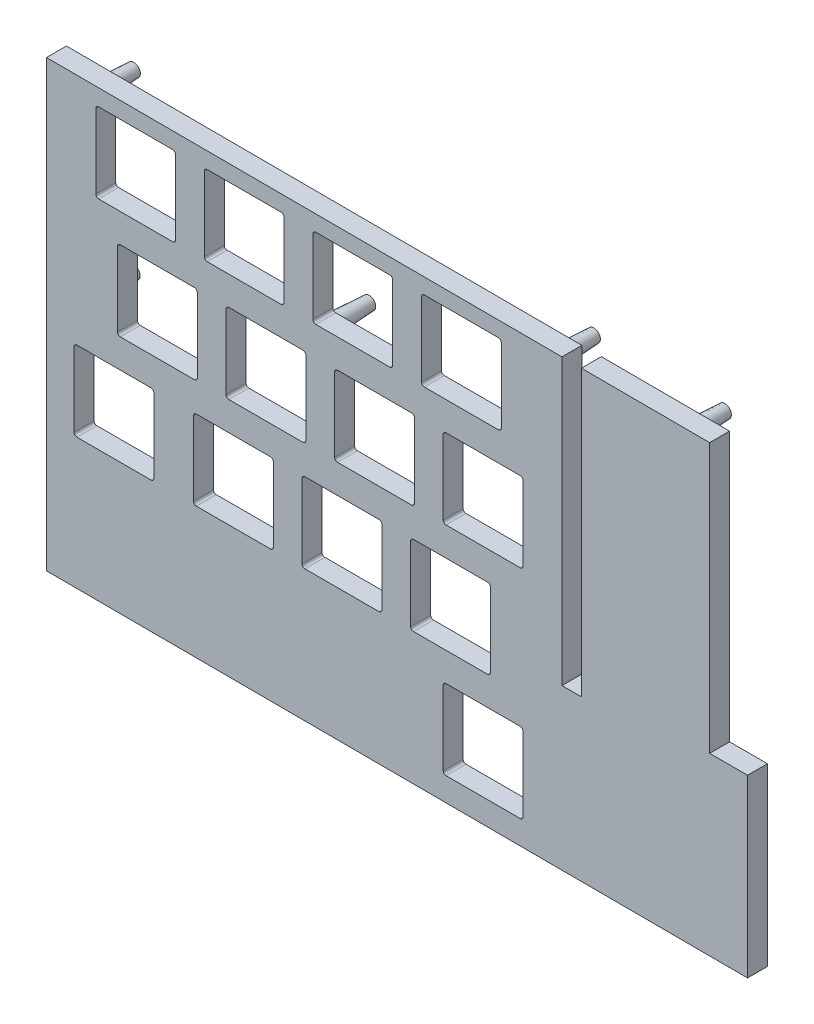
SolidWorks part; units mm, degrees
ref_plane "Front Plane" through (0, 0, 0) normal (0, 0, 1) x (1, 0, 0)
ref_plane "Top Plane" through (0, 0, 0) normal (0, 1, 0) x (1, 0, 0)
ref_plane "Right Plane" through (0, 0, 0) normal (1, 0, 0) x (0, 0, -1)
sketch "Model" plane through (0, 0, 0) normal (0, 0, 1) x (1, 0, 0)
  line L0 (9.145, -2.923) -> (22.145, -2.923)
  line L1 (9.145, -16.923) -> (22.145, -16.923)
  line L2 (8.645, -3.423) -> (8.645, -16.423)
  line L3 (22.645, -3.423) -> (22.645, -16.423)
  line L4 (28.195, -2.923) -> (41.195, -2.923)
  line L5 (28.195, -16.923) -> (41.195, -16.923)
  line L6 (27.695, -3.423) -> (27.695, -16.423)
  line L7 (41.695, -3.423) -> (41.695, -16.423)
  line L8 (47.245, -2.923) -> (60.245, -2.923)
  line L9 (47.245, -16.923) -> (60.245, -16.923)
  line L10 (46.745, -3.423) -> (46.745, -16.423)
  line L11 (60.745, -3.423) -> (60.745, -16.423)
  line L12 (66.295, -2.923) -> (79.295, -2.923)
  line L13 (66.295, -16.923) -> (79.295, -16.923)
  line L14 (65.795, -3.423) -> (65.795, -16.423)
  line L15 (79.795, -3.423) -> (79.795, -16.423)
  line L16 (12.955, -21.973) -> (25.955, -21.973)
  line L17 (12.955, -35.973) -> (25.955, -35.973)
  line L18 (12.455, -22.473) -> (12.455, -35.473)
  line L19 (26.455, -22.473) -> (26.455, -35.473)
  line L20 (32.005, -21.973) -> (45.005, -21.973)
  line L21 (32.005, -35.973) -> (45.005, -35.973)
  line L22 (31.505, -22.473) -> (31.505, -35.473)
  line L23 (45.505, -22.473) -> (45.505, -35.473)
  line L24 (51.055, -21.973) -> (64.055, -21.973)
  line L25 (51.055, -35.973) -> (64.055, -35.973)
  line L26 (50.555, -22.473) -> (50.555, -35.473)
  line L27 (64.555, -22.473) -> (64.555, -35.473)
  line L28 (70.105, -21.973) -> (83.105, -21.973)
  line L29 (70.105, -35.973) -> (83.105, -35.973)
  line L30 (69.605, -22.473) -> (69.605, -35.473)
  line L31 (83.605, -22.473) -> (83.605, -35.473)
  line L32 (5.335, -41.023) -> (18.335, -41.023)
  line L33 (5.335, -55.023) -> (18.335, -55.023)
  line L34 (4.835, -41.523) -> (4.835, -54.523)
  line L35 (18.835, -41.523) -> (18.835, -54.523)
  line L36 (26.29, -41.023) -> (39.29, -41.023)
  line L37 (26.29, -55.023) -> (39.29, -55.023)
  line L38 (25.79, -41.523) -> (25.79, -54.523)
  line L39 (39.79, -41.523) -> (39.79, -54.523)
  line L40 (45.34, -41.023) -> (58.34, -41.023)
  line L41 (45.34, -55.023) -> (58.34, -55.023)
  line L42 (44.84, -41.523) -> (44.84, -54.523)
  line L43 (58.84, -41.523) -> (58.84, -54.523)
  line L44 (64.39, -41.023) -> (77.39, -41.023)
  line L45 (64.39, -55.023) -> (77.39, -55.023)
  line L46 (63.89, -41.523) -> (63.89, -54.523)
  line L47 (77.89, -41.523) -> (77.89, -54.523)
  line L48 (70.105, -60.073) -> (83.105, -60.073)
  line L49 (70.105, -74.073) -> (83.105, -74.073)
  line L50 (69.605, -60.573) -> (69.605, -73.573)
  line L51 (83.605, -60.573) -> (83.605, -73.573)
  line L52 (61.667, -61.073) -> (67.667, -61.073)
  line L53 (61.667, -76.073) -> (67.667, -76.073)
  line L54 (61.167, -61.573) -> (61.167, -75.573)
  line L55 (68.167, -61.573) -> (68.167, -75.573)
  line L56 (85.543, -61.073) -> (91.543, -61.073)
  line L57 (85.543, -76.073) -> (91.543, -76.073)
  line L58 (85.043, -61.573) -> (85.043, -75.573)
  line L59 (92.043, -61.573) -> (92.043, -75.573)
  line L60 (0, -78) -> (123, -78.3615)
  line L61 (0, 0) -> (123, -0.3615)
  line L62 (0, -78) -> (0, 0)
  line L63 (123, -78.3615) -> (123, -0.3615)
  arc A0 (9.145, -2.923) -> (8.645, -3.423) centre (9.145, -3.423) ccw
  arc A1 (22.645, -3.423) -> (22.145, -2.923) centre (22.145, -3.423) ccw
  arc A2 (8.645, -16.423) -> (9.145, -16.923) centre (9.145, -16.423) ccw
  arc A3 (22.145, -16.923) -> (22.645, -16.423) centre (22.145, -16.423) ccw
  arc A4 (28.195, -2.923) -> (27.695, -3.423) centre (28.195, -3.423) ccw
  arc A5 (41.695, -3.423) -> (41.195, -2.923) centre (41.195, -3.423) ccw
  arc A6 (27.695, -16.423) -> (28.195, -16.923) centre (28.195, -16.423) ccw
  arc A7 (41.195, -16.923) -> (41.695, -16.423) centre (41.195, -16.423) ccw
  arc A8 (47.245, -2.923) -> (46.745, -3.423) centre (47.245, -3.423) ccw
  arc A9 (60.745, -3.423) -> (60.245, -2.923) centre (60.245, -3.423) ccw
  arc A10 (46.745, -16.423) -> (47.245, -16.923) centre (47.245, -16.423) ccw
  arc A11 (60.245, -16.923) -> (60.745, -16.423) centre (60.245, -16.423) ccw
  arc A12 (66.295, -2.923) -> (65.795, -3.423) centre (66.295, -3.423) ccw
  arc A13 (79.795, -3.423) -> (79.295, -2.923) centre (79.295, -3.423) ccw
  arc A14 (65.795, -16.423) -> (66.295, -16.923) centre (66.295, -16.423) ccw
  arc A15 (79.295, -16.923) -> (79.795, -16.423) centre (79.295, -16.423) ccw
  arc A16 (12.955, -21.973) -> (12.455, -22.473) centre (12.955, -22.473) ccw
  arc A17 (26.455, -22.473) -> (25.955, -21.973) centre (25.955, -22.473) ccw
  arc A18 (12.455, -35.473) -> (12.955, -35.973) centre (12.955, -35.473) ccw
  arc A19 (25.955, -35.973) -> (26.455, -35.473) centre (25.955, -35.473) ccw
  arc A20 (32.005, -21.973) -> (31.505, -22.473) centre (32.005, -22.473) ccw
  arc A21 (45.505, -22.473) -> (45.005, -21.973) centre (45.005, -22.473) ccw
  arc A22 (31.505, -35.473) -> (32.005, -35.973) centre (32.005, -35.473) ccw
  arc A23 (45.005, -35.973) -> (45.505, -35.473) centre (45.005, -35.473) ccw
  arc A24 (51.055, -21.973) -> (50.555, -22.473) centre (51.055, -22.473) ccw
  arc A25 (64.555, -22.473) -> (64.055, -21.973) centre (64.055, -22.473) ccw
  arc A26 (50.555, -35.473) -> (51.055, -35.973) centre (51.055, -35.473) ccw
  arc A27 (64.055, -35.973) -> (64.555, -35.473) centre (64.055, -35.473) ccw
  arc A28 (70.105, -21.973) -> (69.605, -22.473) centre (70.105, -22.473) ccw
  arc A29 (83.605, -22.473) -> (83.105, -21.973) centre (83.105, -22.473) ccw
  arc A30 (69.605, -35.473) -> (70.105, -35.973) centre (70.105, -35.473) ccw
  arc A31 (83.105, -35.973) -> (83.605, -35.473) centre (83.105, -35.473) ccw
  arc A32 (5.335, -41.023) -> (4.835, -41.523) centre (5.335, -41.523) ccw
  arc A33 (18.835, -41.523) -> (18.335, -41.023) centre (18.335, -41.523) ccw
  arc A34 (4.835, -54.523) -> (5.335, -55.023) centre (5.335, -54.523) ccw
  arc A35 (18.335, -55.023) -> (18.835, -54.523) centre (18.335, -54.523) ccw
  arc A36 (26.29, -41.023) -> (25.79, -41.523) centre (26.29, -41.523) ccw
  arc A37 (39.79, -41.523) -> (39.29, -41.023) centre (39.29, -41.523) ccw
  arc A38 (25.79, -54.523) -> (26.29, -55.023) centre (26.29, -54.523) ccw
  arc A39 (39.29, -55.023) -> (39.79, -54.523) centre (39.29, -54.523) ccw
  arc A40 (45.34, -41.023) -> (44.84, -41.523) centre (45.34, -41.523) ccw
  arc A41 (58.84, -41.523) -> (58.34, -41.023) centre (58.34, -41.523) ccw
  arc A42 (44.84, -54.523) -> (45.34, -55.023) centre (45.34, -54.523) ccw
  arc A43 (58.34, -55.023) -> (58.84, -54.523) centre (58.34, -54.523) ccw
  arc A44 (64.39, -41.023) -> (63.89, -41.523) centre (64.39, -41.523) ccw
  arc A45 (77.89, -41.523) -> (77.39, -41.023) centre (77.39, -41.523) ccw
  arc A46 (63.89, -54.523) -> (64.39, -55.023) centre (64.39, -54.523) ccw
  arc A47 (77.39, -55.023) -> (77.89, -54.523) centre (77.39, -54.523) ccw
  arc A48 (70.105, -60.073) -> (69.605, -60.573) centre (70.105, -60.573) ccw
  arc A49 (83.605, -60.573) -> (83.105, -60.073) centre (83.105, -60.573) ccw
  arc A50 (69.605, -73.573) -> (70.105, -74.073) centre (70.105, -73.573) ccw
  arc A51 (83.105, -74.073) -> (83.605, -73.573) centre (83.105, -73.573) ccw
  arc A52 (61.667, -61.073) -> (61.167, -61.573) centre (61.667, -61.573) ccw
  arc A53 (68.167, -61.573) -> (67.667, -61.073) centre (67.667, -61.573) ccw
  arc A54 (61.167, -75.573) -> (61.667, -76.073) centre (61.667, -75.573) ccw
  arc A55 (67.667, -76.073) -> (68.167, -75.573) centre (67.667, -75.573) ccw
  arc A56 (85.543, -61.073) -> (85.043, -61.573) centre (85.543, -61.573) ccw
  arc A57 (92.043, -61.573) -> (91.543, -61.073) centre (91.543, -61.573) ccw
  arc A58 (85.043, -75.573) -> (85.543, -76.073) centre (85.543, -75.573) ccw
  arc A59 (91.543, -76.073) -> (92.043, -75.573) centre (91.543, -75.573) ccw
  dimension "D1" = 78
  dimension "D2" = 123
extrude "Boss-Extrude1" add sketch "Model" along normal blind 3.5
sketch "Sketch3" plane through (0, 0, 3.5) normal (0, 0, 1) x (1, 0, 0)
  line L0 (0, 0) -> (123, -0.3615) construction
  line L1 (90.4342, -0.2658) -> (93.8447, -0.2658)
  line L2 (90.4342, -0.2658) -> (90.4342, -50.2113)
  line L3 (90.4342, -50.2113) -> (93.8447, -50.2113)
  line L4 (93.8447, -0.2658) -> (93.8447, -50.2113)
  line L5 (123, -78.3615) -> (123, -0.3615) construction
  line L6 (116.3518, -0.3419) -> (123, -0.3419)
  line L7 (116.3518, -0.3419) -> (116.3518, -47.5526)
  line L8 (116.3518, -47.5526) -> (123, -47.5526)
  line L9 (123, -0.3419) -> (123, -47.5526)
extrude "Cut-Extrude2" cut sketch "Sketch3" against normal blind 5
sketch "Sketch4" plane through (0, 0, 0) normal (0, 0, 1) x (1, 0, 0)
  circle A0 centre (104.7576, -16.1304) radius 3.5444
  circle A1 centre (104.7576, -16.1304) radius 2.3691
extrude "Boss-Extrude2" add sketch "Sketch4" against normal blind 8
sketch "Sketch6" plane through (0, 0, 0) normal (0, 0, -1) x (-1, 0, 0)
  circle A0 centre (-4.835, -70.1004) radius 1.5
  circle A1 centre (-58.6385, -70.1004) radius 1.4852
  circle A2 centre (-112.442, -70.1004) radius 1.5021
  circle A3 centre (-108.5181, -4.704) radius 1.509
  circle A4 centre (-85.543, -4.704) radius 1.5
  circle A5 centre (-46.125, -19.448) radius 1.5
  circle A6 centre (-4.835, -4.704) radius 1.5
  circle A7 centre (-4.835, -35.4526) radius 1.4797
  circle A8 centre (-108.5181, -4.704) radius 0.2482
  circle A9 centre (-85.543, -4.704) radius 0.268
  circle A10 centre (-46.125, -19.448) radius 0.2611
  circle A11 centre (-4.835, -4.704) radius 0.2453
  circle A12 centre (-4.835, -35.4526) radius 0.2681
  circle A13 centre (-4.835, -70.1004) radius 0.1765
  circle A14 centre (-58.6385, -70.1004) radius 0.2079
  circle A15 centre (-112.442, -70.1004) radius 0.196
extrude "Boss-Extrude3" add sketch "Sketch6" along normal blind 7 draft 3
fillet "Fillet1" radius 1 9 edges at (6.335, -4.704, 0) (6.3147, -35.4526, 0) (6.335, -70.1004, 0) (113.9441, -70.1004, 0) (60.1237, -70.1004, 0) (47.625, -19.448, 0) (108.302, -16.1304, 0) (110.0272, -4.704, 0) (87.043, -4.704, 0)
